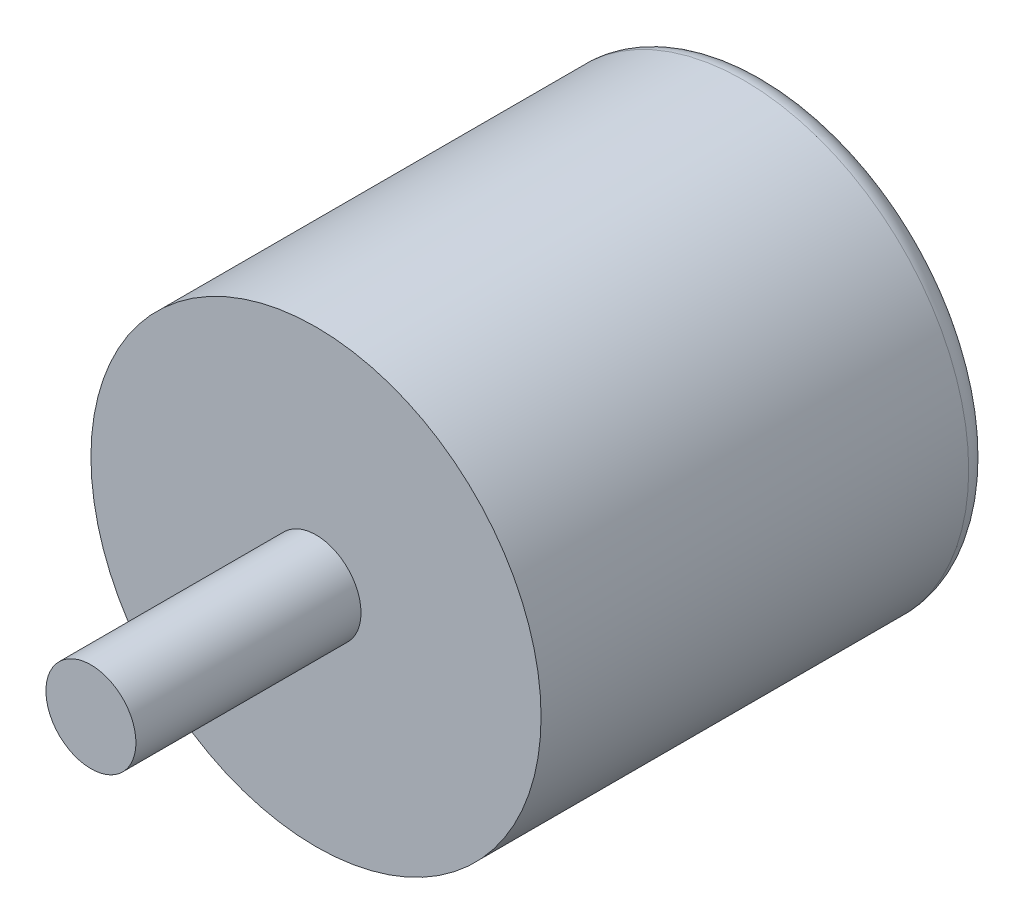
SolidWorks part; units mm, degrees
material "Chromium Copper, UNS C18200"
ref_plane "Front Plane" through (0, 0, 0) normal (0, 0, 1) x (1, 0, 0)
ref_plane "Top Plane" through (0, 0, 0) normal (0, 1, 0) x (1, 0, 0)
ref_plane "Right Plane" through (0, 0, 0) normal (1, 0, 0) x (0, 0, -1)
sketch "Sketch1" plane through (0, 0, 0) normal (0, 0, 1) x (1, 0, 0)
  circle A0 centre (0, 0) radius 12.7
  dimension "D1" = 25.4
extrude "Boss-Extrude1" add sketch "Sketch1" along normal blind 25.4
sketch "Sketch2" plane through (0, 0, 25.4) normal (0, 0, 1) x (1, 0, 0)
  circle A0 centre (0, 0) radius 2.54
  dimension "D1" = 5.08
extrude "Boss-Extrude2" add sketch "Sketch2" along normal blind 12.7
fillet "Fillet1" radius 1.27 1 edges at (12.7, 0, 0)
